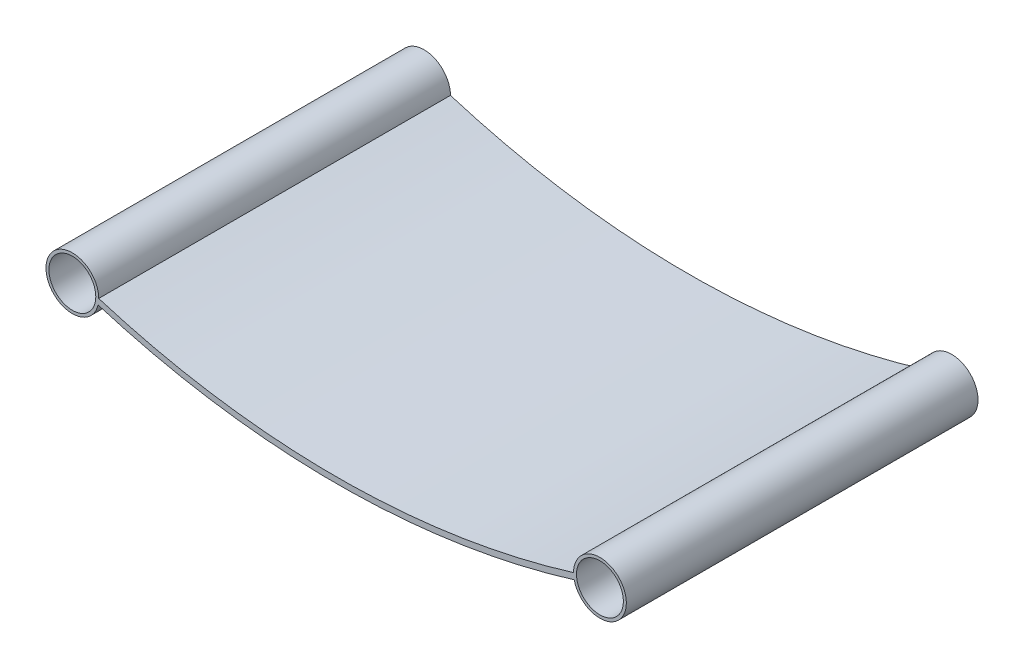
SolidWorks part; units mm, degrees
ref_plane "Front Plane" through (0, 0, 0) normal (0, 0, 1) x (1, 0, 0)
ref_plane "Top Plane" through (0, 0, 0) normal (0, 1, 0) x (1, 0, 0)
ref_plane "Right Plane" through (0, 0, 0) normal (1, 0, 0) x (0, 0, -1)
sketch "Sketch2" plane through (0, 0, 0) normal (0, 0, 1) x (1, 0, 0)
  circle A0 centre (45, 0) radius 4
  circle A1 centre (-45, 0) radius 4
  circle A2 centre (-45, 0) radius 4.5
  circle A3 centre (45, 0) radius 4.5
  point P4 (0, 0)
  dimension "D1" = 9
  dimension "D2" = 8
  dimension "D3" = 8
  dimension "D4" = 9
  dimension "D5" = 90
extrude "Boss-Extrude1" add sketch "Sketch2" against normal blind 60
sketch "Sketch3" plane through (0, 0, 0) normal (0, 0, 1) x (1, 0, 0)
  line L0 (40.5, 0) -> (40.7938, -0.9559)
  line L1 (-40.5, 0) -> (-40.7938, -0.9559)
  arc A0 (40.5, 0) -> (-40.5, 0) centre (0, 131.7814) cw
  circle A1 centre (45, 0) radius 4.5 construction
  circle A2 centre (-45, 0) radius 4.5 construction
  arc A3 (40.7938, -0.9559) -> (-40.7938, -0.9559) centre (0, 131.7814) cw
  dimension "D1" = 1
extrude "Boss-Extrude2" add sketch "Sketch3" against normal blind 60
